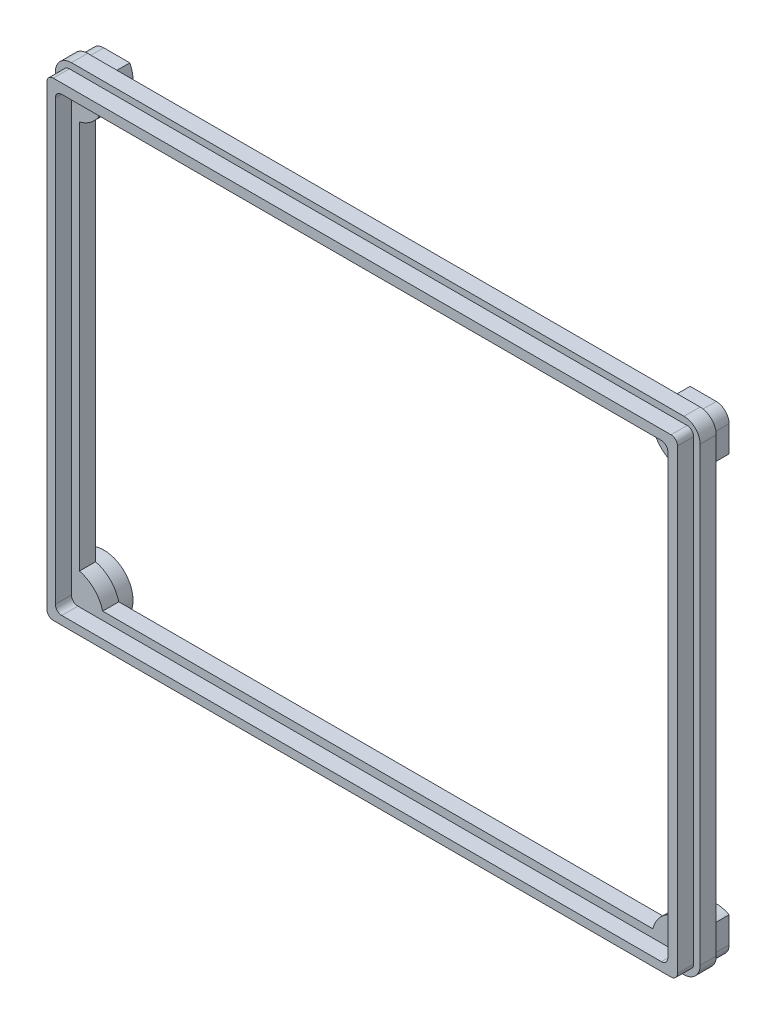
SolidWorks part; units mm, degrees
ref_plane "Plano frontal" through (0, 0, 0) normal (0, 0, 1) x (1, 0, 0)
ref_plane "Plano superior" through (0, 0, 0) normal (0, 1, 0) x (1, 0, 0)
ref_plane "Plano direito" through (0, 0, 0) normal (1, 0, 0) x (0, 0, -1)
sketch "Esboço3" plane through (0, 0, 0) normal (0, 0, 1) x (1, 0, 0)
  line L2 (-89.5878, 33.5889) -> (100.4122, 33.5889)
  line L3 (-79.9053, 26.0889) -> (90.7297, 26.0889)
  line L6 (-94.5878, 28.5889) -> (-94.5878, -111.4111)
  line L11 (-79.9053, -108.9111) -> (90.7297, -108.9111)
  line L12 (105.4122, 28.5889) -> (105.4122, -111.4111)
  line L13 (97.9122, -101.7286) -> (97.9122, 18.9064)
  line L14 (100.4122, -116.4111) -> (-89.5878, -116.4111)
  line L16 (-87.0878, 18.9064) -> (-87.0878, -101.7286)
  arc A0 (-80.9275, 33.5889) -> (-94.5878, 19.9286) centre (-89.5878, 28.5889) cw
  arc A1 (-94.5878, 28.5889) -> (-89.5878, 33.5889) centre (-89.5878, 28.5889) cw
  arc A2 (91.752, 33.5889) -> (105.4122, 19.9286) centre (100.4122, 28.5889) ccw
  arc A3 (100.4122, 33.5889) -> (105.4122, 28.5889) centre (100.4122, 28.5889) cw
  arc A4 (105.4122, -102.7508) -> (91.752, -116.4111) centre (100.4122, -111.4111) ccw
  arc A5 (105.4122, -111.4111) -> (100.4122, -116.4111) centre (100.4122, -111.4111) cw
  arc A6 (-94.5878, -102.7508) -> (-80.9275, -116.4111) centre (-89.5878, -111.4111) cw
  arc A7 (-94.5878, -111.4111) -> (-89.5878, -116.4111) centre (-89.5878, -111.4111) ccw
sketch "Esboço4" plane through (0, 0, 0) normal (0, 0, 1) x (1, 0, 0)
  line L8 (-94.5878, 19.9286) -> (-94.5878, 28.5889)
  line L10 (-89.5878, 33.5889) -> (-80.9275, 33.5889)
  line L11 (91.752, 33.5889) -> (100.4122, 33.5889)
  line L12 (105.4122, 28.5889) -> (105.4122, 19.9286)
  line L13 (105.4122, -102.7508) -> (105.4122, -111.4111)
  line L14 (100.4122, -116.4111) -> (91.752, -116.4111)
  line L15 (-80.9275, -116.4111) -> (-89.5878, -116.4111)
  line L16 (-94.5878, -111.4111) -> (-94.5878, -102.7508)
  arc A0 (-80.9275, 33.5889) -> (-94.5878, 19.9286) centre (-89.5878, 28.5889) cw
  arc A1 (91.752, 33.5889) -> (105.4122, 19.9286) centre (100.4122, 28.5889) ccw
  arc A2 (105.4122, -102.7508) -> (91.752, -116.4111) centre (100.4122, -111.4111) ccw
  arc A3 (-80.9275, -116.4111) -> (-94.5878, -102.7508) centre (-89.5878, -111.4111) ccw
  arc A4 (-89.5878, 33.5889) -> (-94.5878, 28.5889) centre (-89.5878, 28.5889) ccw
  arc A5 (100.4122, 33.5889) -> (105.4122, 28.5889) centre (100.4122, 28.5889) cw
  arc A6 (105.4122, -111.4111) -> (100.4122, -116.4111) centre (100.4122, -111.4111) cw
  arc A7 (-94.5878, -111.4111) -> (-89.5878, -116.4111) centre (-89.5878, -111.4111) ccw
extrude "Ressalto-extrusão1" add sketch "Esboço4" against normal blind 10
sketch "Esboço5" plane through (0, 0, 0) normal (0, 0, 1) x (1, 0, 0)
  line L0 (-87.0878, 18.9064) -> (-87.0878, -101.7286)
  line L1 (-94.5878, -102.7508) -> (-94.5878, 19.9286)
  line L2 (-80.9275, -116.4111) -> (91.752, -116.4111)
  line L3 (-79.9053, -108.9111) -> (90.7297, -108.9111)
  line L4 (97.9122, 18.9064) -> (97.9122, -101.7286)
  line L5 (105.4122, -102.7508) -> (105.4122, 19.9286)
  line L6 (90.7297, 26.0889) -> (-79.9053, 26.0889)
  line L7 (-80.9275, 33.5889) -> (91.752, 33.5889)
  arc A0 (-94.5878, 19.9286) -> (-87.0878, 18.9064) centre (-89.5878, 28.5889) ccw
  arc A1 (-94.5878, -102.7508) -> (-87.0878, -101.7286) centre (-89.5878, -111.4111) cw
  arc A2 (-79.9053, -108.9111) -> (-80.9275, -116.4111) centre (-89.5878, -111.4111) cw
  arc A3 (90.7297, -108.9111) -> (91.752, -116.4111) centre (100.4122, -111.4111) ccw
  arc A4 (97.9122, -101.7286) -> (105.4122, -102.7508) centre (100.4122, -111.4111) cw
  arc A5 (97.9122, 18.9064) -> (105.4122, 19.9286) centre (100.4122, 28.5889) ccw
  arc A6 (91.752, 33.5889) -> (90.7297, 26.0889) centre (100.4122, 28.5889) ccw
  arc A7 (-80.9275, 33.5889) -> (-79.9053, 26.0889) centre (-89.5878, 28.5889) cw
extrude "Ressalto-extrusão2" add sketch "Esboço5" against normal blind 5 separate body
sketch "Esboço6" plane through (0, 0, -10) normal (0, 0, -1) x (-1, 0, 0)
  line L2 (-91.752, 33.5889) -> (-91.752, 32.5889)
  line L3 (-100.4122, 33.5889) -> (-100.4122, 32.5889)
  line L4 (-100.4122, 32.5889) -> (-91.752, 32.5889)
  line L5 (-105.4122, 28.5889) -> (-104.4122, 28.5889)
  line L6 (-105.4122, 19.9286) -> (-104.4122, 19.9286)
  line L7 (-104.4122, 19.9286) -> (-104.4122, 28.5889)
  line L8 (-105.4122, 28.5889) -> (-105.4122, 19.9286)
  line L9 (-100.4122, 33.5889) -> (-91.752, 33.5889)
  line L10 (89.5878, 33.5889) -> (89.5878, 32.5889)
  line L11 (80.9275, 33.5889) -> (80.9275, 32.5889)
  line L12 (80.9275, 32.5889) -> (89.5878, 32.5889)
  line L13 (80.9275, 33.5889) -> (89.5878, 33.5889)
  line L14 (94.5878, 28.5889) -> (93.5878, 28.5889)
  line L15 (94.5878, 28.5889) -> (94.5878, 19.9286)
  line L16 (94.5878, 19.9286) -> (93.5878, 19.9286)
  line L17 (93.5878, 28.5889) -> (93.5878, 19.9286)
  line L23 (94.5878, -102.7508) -> (93.5878, -102.7508)
  line L24 (94.5878, -102.7508) -> (94.5878, -111.4061)
  line L25 (94.5878, -111.4061) -> (93.5878, -111.4061)
  line L26 (93.5878, -102.7508) -> (93.5878, -111.4061)
  line L27 (89.5878, -116.4111) -> (80.9275, -116.4111)
  line L28 (89.5878, -116.4111) -> (89.5878, -115.4111)
  line L29 (89.5878, -115.4111) -> (80.9275, -115.4111)
  line L30 (80.9275, -116.4111) -> (80.9275, -115.4111)
  line L31 (-91.752, -116.4111) -> (-100.4122, -116.4111)
  line L32 (-91.752, -116.4111) -> (-91.752, -115.4111)
  line L33 (-91.752, -115.4111) -> (-100.4122, -115.4111)
  line L34 (-100.4122, -116.4111) -> (-100.4122, -115.4111)
  line L35 (-105.4122, -102.7508) -> (-104.4122, -102.7508)
  line L36 (-105.4122, -102.7508) -> (-105.4122, -111.4061)
  line L37 (-105.4122, -111.4061) -> (-104.4122, -111.4061)
  line L38 (-104.4122, -102.7508) -> (-104.4122, -111.4061)
  dimension "D1" = 1
  dimension "D2" = 1
  dimension "D3" = 1
  dimension "D4" = 1
  dimension "D5" = 1
  dimension "D6" = 1
  dimension "D7" = 1
  dimension "D8" = 1
extrude "Corte-extrusão2" cut sketch "Esboço6" against normal blind 5
sketch "Esboço7" plane through (0, 0, -10) normal (0, 0, -1) x (-1, 0, 0)
  line L16 (-104.4122, 20.4788) -> (-104.4122, 19.9286)
  line L17 (-104.4122, 19.9286) -> (-105.4122, 19.9286)
  line L18 (80.9275, 33.5889) -> (80.9275, 32.5889)
  line L19 (-91.752, 33.5889) -> (-91.752, 32.5889)
  line L20 (-91.752, 32.5889) -> (-92.3021, 32.5889)
  line L21 (-100.4122, 32.5889) -> (-91.752, 32.5889) construction
  line L22 (80.9275, 32.5889) -> (81.4781, 32.5889)
  line L23 (80.9275, 32.5889) -> (89.5878, 32.5889) construction
  line L24 (94.5878, 19.9286) -> (93.5878, 19.9286)
  line L25 (93.5878, 19.9286) -> (93.5878, 20.4792)
  line L26 (93.5878, 28.5889) -> (93.5878, 19.9286) construction
  line L27 (94.5878, -102.7508) -> (93.5878, -102.7508)
  line L28 (93.5878, -102.7508) -> (93.5878, -103.3009)
  line L29 (93.5878, -102.7508) -> (93.5878, -111.4061) construction
  line L30 (89.5878, -115.4111) -> (80.9275, -115.4111) construction
  line L31 (81.4776, -115.4111) -> (80.9275, -115.4111)
  line L32 (80.9275, -115.4111) -> (80.9275, -116.4111)
  line L33 (-105.4122, -102.7508) -> (-104.4122, -102.7508)
  line L34 (-104.4122, -102.7508) -> (-104.4122, -103.301)
  line L35 (-104.4122, -111.4061) -> (-104.4122, -102.7508) construction
  line L36 (-91.752, -116.4111) -> (-91.752, -115.4111)
  line L37 (-91.752, -115.4111) -> (-92.3021, -115.4111)
  line L38 (-91.752, -115.4111) -> (-100.4122, -115.4111) construction
  arc A2 (-91.752, 33.5889) -> (-105.4122, 19.9286) centre (-100.4122, 28.5889) cw
  arc A10 (-105.4122, -102.7508) -> (-91.752, -116.4111) centre (-100.4122, -111.4111) cw
  arc A12 (80.9275, -116.4111) -> (94.5878, -102.7508) centre (89.5878, -111.4111) cw
  arc A14 (80.9275, 33.5889) -> (94.5878, 19.9286) centre (89.5878, 28.5889) ccw
  arc A16 (-104.4122, 20.4788) -> (-92.3021, 32.5889) centre (-100.3099, 28.4866) ccw
  arc A17 (81.4781, 32.5889) -> (93.5878, 20.4792) centre (89.4918, 28.4929) ccw
  arc A18 (81.4776, -115.4111) -> (93.5878, -103.3009) centre (89.4841, -111.3074) cw
  arc A19 (-104.4122, -103.301) -> (-92.3021, -115.4111) centre (-100.3092, -111.3081) cw
extrude "Corte-extrusão10" cut sketch "Esboço7" against normal blind 5
sketch "Esboço8" plane through (0, 0, 0) normal (0, 0, -1) x (-1, 0, 0)
  line L0 (-105.4122, 28.5889) -> (-104.4122, 28.5889)
  line L1 (-100.4122, 33.5889) -> (-100.4122, 32.5889)
  line L2 (89.5878, 33.5889) -> (89.5878, 32.5889)
  line L3 (94.5878, 28.5889) -> (93.5878, 28.5889)
  line L4 (94.5878, -111.4111) -> (93.5878, -111.4061)
  line L5 (89.5878, -115.4111) -> (89.5878, -116.4111)
  line L6 (-104.4122, -111.4061) -> (-105.4122, -111.4111)
  line L7 (-100.4122, -116.4111) -> (-100.4122, -115.4111)
  arc A0 (-105.4122, 28.5889) -> (-100.4122, 33.5889) centre (-100.4122, 28.5889) cw
  arc A1 (-100.4122, 32.5889) -> (-104.4122, 28.5889) centre (-100.4122, 28.5889) ccw
  arc A2 (89.5878, 33.5889) -> (94.5878, 28.5889) centre (89.5878, 28.5889) cw
  arc A3 (89.5878, 32.5889) -> (93.5878, 28.5889) centre (89.5878, 28.5889) cw
  arc A4 (89.5878, -116.4111) -> (94.5878, -111.4111) centre (89.5878, -111.4111) ccw
  arc A5 (89.5878, -115.4111) -> (93.5878, -111.4061) centre (89.5853, -111.4086) ccw
  arc A6 (-104.4122, -111.4061) -> (-100.4122, -115.4111) centre (-100.4097, -111.4086) ccw
  arc A7 (-105.4122, -111.4111) -> (-100.4122, -116.4111) centre (-100.4122, -111.4111) ccw
sketch "Esboço9" plane through (0, 0, -10) normal (0, 0, -1) x (-1, 0, 0)
  line L0 (-104.4122, 28.5889) -> (-105.4122, 28.5889)
  line L1 (-100.4122, 32.5889) -> (-100.4122, 33.5889)
  arc A0 (-105.4122, 28.5889) -> (-100.4122, 33.5889) centre (-100.4122, 28.5889) cw
  arc A1 (-104.4122, 28.5889) -> (-100.4122, 32.5889) centre (-100.4122, 28.5889) cw
extrude "Corte-extrusão11" cut sketch "Esboço9" against normal blind 5
sketch "Esboço10" plane through (0, 0, -10) normal (0, 0, -1) x (-1, 0, 0)
  line L0 (89.5878, 33.5889) -> (89.5878, 32.5889)
  line L1 (94.5878, 28.5889) -> (93.5878, 28.5889)
  arc A0 (89.5878, 33.5889) -> (94.5878, 28.5889) centre (89.5878, 28.5889) cw
  arc A1 (89.5878, 32.5889) -> (93.5878, 28.5889) centre (89.5878, 28.5889) cw
extrude "Corte-extrusão12" cut sketch "Esboço10" against normal blind 5
sketch "Esboço12" plane through (0, 0, -10) normal (0, 0, -1) x (-1, 0, 0)
  line L0 (-105.4122, -111.4061) -> (-104.4122, -111.4061)
  line L1 (-100.4122, -115.4111) -> (-100.4122, -116.4111)
  arc A0 (-104.4122, -111.4061) -> (-100.4122, -115.4111) centre (-100.4097, -111.4086) ccw
  arc A1 (-105.4122, -111.4061) -> (-100.4122, -116.4111) centre (-100.4122, -111.4111) ccw
extrude "Corte-extrusão15" cut sketch "Esboço12" against normal blind 5
sketch "Esboço13" plane through (0, 0, -10) normal (0, 0, -1) x (-1, 0, 0)
  line L5 (89.5878, -115.4111) -> (89.5878, -116.4111) construction
  line L7 (94.5878, -111.4111) -> (93.5878, -111.4061) construction
  line L10 (89.5878, -115.9187) -> (89.5878, -116.4111)
  line L11 (94.5878, -111.4111) -> (94.0878, -111.4086)
  arc A5 (94.0878, -111.4086) -> (89.5878, -115.9187) centre (89.5827, -111.4137) cw
  arc A6 (94.5878, -111.4111) -> (89.5878, -116.4111) centre (89.5878, -111.4111) cw
extrude "Corte-extrusão23" cut sketch "Esboço13" against normal blind 5
sketch "Esboço14" plane through (0, 0, -10) normal (0, 0, -1) x (-1, 0, 0)
  line L5 (89.5878, -115.4111) -> (89.5878, -116.0072)
  line L6 (89.5878, -115.4111) -> (89.5878, -116.4111) construction
  line L7 (89.5878, -116.0072) -> (93.5878, -115.5795)
  line L8 (93.5878, -111.4061) -> (94.6474, -111.3592)
  line L10 (94.6474, -111.3592) -> (94.4184, -115.5795)
  line L11 (94.4184, -115.5795) -> (93.5878, -115.5795)
  arc A0 (93.5878, -111.4061) -> (89.5878, -115.4111) centre (89.5853, -111.4086) cw
extrude "Corte-extrusão24" cut sketch "Esboço14" against normal blind 5
sketch "Esboço15" plane through (0, 0, 0) normal (0, 0, 1) x (1, 0, 0)
  line L1 (-92.2049, 31.6139) -> (103.3997, 31.6139)
  line L2 (-92.2049, 31.6139) -> (-92.2049, -114.0694)
  line L3 (-92.2049, -114.0694) -> (103.3997, -114.0694)
  line L4 (103.3997, 31.6139) -> (103.3997, -114.0694)
  arc A0 (-89.5878, 32.5889) -> (-93.5878, 28.5889) centre (-89.5878, 28.5889) ccw construction
  arc A1 (100.4122, -115.4111) -> (104.4122, -111.4061) centre (100.4097, -111.4086) ccw construction
extrude "Ressalto-extrusão3" add sketch "Esboço15" along normal blind 5
sketch "Esboço16" plane through (0, 0, 5) normal (0, 0, 1) x (1, 0, 0)
  line L1 (-89.5878, 28.5889) -> (100.4122, 28.5889)
  line L2 (-89.5878, 28.5889) -> (-89.5878, -111.4111)
  line L3 (-89.5878, -111.4111) -> (100.4122, -111.4111)
  line L4 (100.4122, 28.5889) -> (100.4122, -111.4111)
extrude "Corte-extrusão25" cut sketch "Esboço16" against normal blind 5
fillet "Filete1" radius 2 1 edges at (103.3997, -114.0694, 2.5)
fillet "Filete2" radius 2 1 edges at (103.3997, 31.6139, 2.5)
fillet "Filete3" radius 2 1 edges at (100.4122, 28.5889, 2.5)
fillet "Filete4" radius 2 1 edges at (100.4122, -111.4111, 2.5)
fillet "Filete5" radius 2 1 edges at (-89.5878, 28.5889, 2.5)
fillet "Filete6" radius 2 1 edges at (-92.2049, 31.6139, 2.5)
fillet "Filete7" radius 2 1 edges at (-92.2049, -114.0694, 2.5)
fillet "Filete8" radius 2 1 edges at (-89.5878, -111.4111, 2.5)
